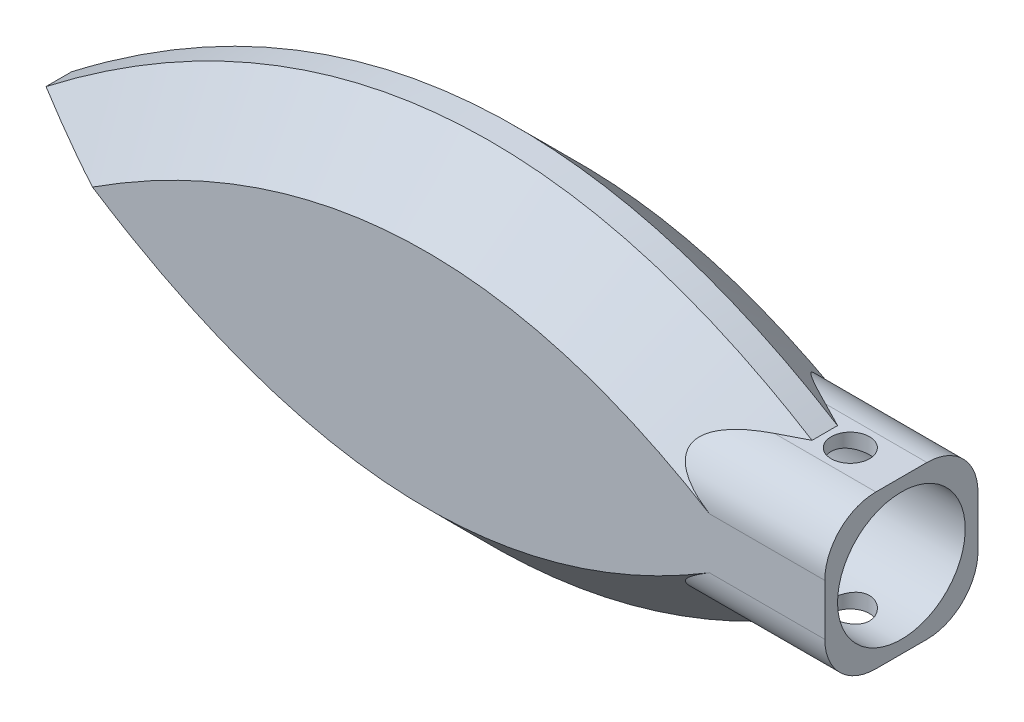
SolidWorks part; units mm, degrees
ref_plane "Ön Düzlem" through (0, 0, 0) normal (0, 0, 1) x (1, 0, 0)
ref_plane "Üst Düzlem" through (0, 0, 0) normal (0, 1, 0) x (1, 0, 0)
ref_plane "Sağ Düzlem" through (0, 0, 0) normal (1, 0, 0) x (0, 0, -1)
sketch "Sketch1" plane through (0, 0, 0) normal (0, 0, 1) x (1, 0, 0)
  line L0 (0, 0) -> (-60, 0) construction
  line L2 (0, 6) -> (6, 6)
  line L3 (6, 6) -> (6, -6)
  line L4 (6, -6) -> (0, -6)
  spline S0 degree 2 poles (0, 6) (-28.9293, 23.9548) (-60, 0) knots 0 0 0 1 1 1
  spline S1 degree 2 poles (0, -6) (-28.9293, -23.9548) (-60, 0) knots 0 0 0 1 1 1
  dimension "D1" = 6
  dimension "D2" = 60
  dimension "D3" = 6
extrude "Boss-Extrude2" add sketch "Sketch1" along normal blind 12
chamfer "Chamfer1" distance 5 angle 45 4 edges
sketch "Sketch2" plane through (6, 0, 0) normal (1, 0, 0) x (0, 0, -1)
  line L0 (-12, 6) -> (0, 6) construction
  line L2 (-12, -6) -> (-12, 6) construction
  circle A0 centre (-6, 0) radius 5
  point P5 (-6, 6)
  point P12 (-12, 0)
  dimension "D1" = 10
extrude "Cut-Extrude1" cut sketch "Sketch2" against normal blind 12
sketch "Sketch3" plane through (0, 6, 0) normal (0, 1, 0) x (1, 0, 0)
  line L0 (6, -12) -> (6, 0) construction
  circle A0 centre (2, -6) radius 1.5
  point P5 (6, -6)
  dimension "D1" = 3
  dimension "D2" = 4
extrude "Cut-Extrude2" cut sketch "Sketch3" against normal blind 21
fillet "Fillet1" radius 4 4 edges
